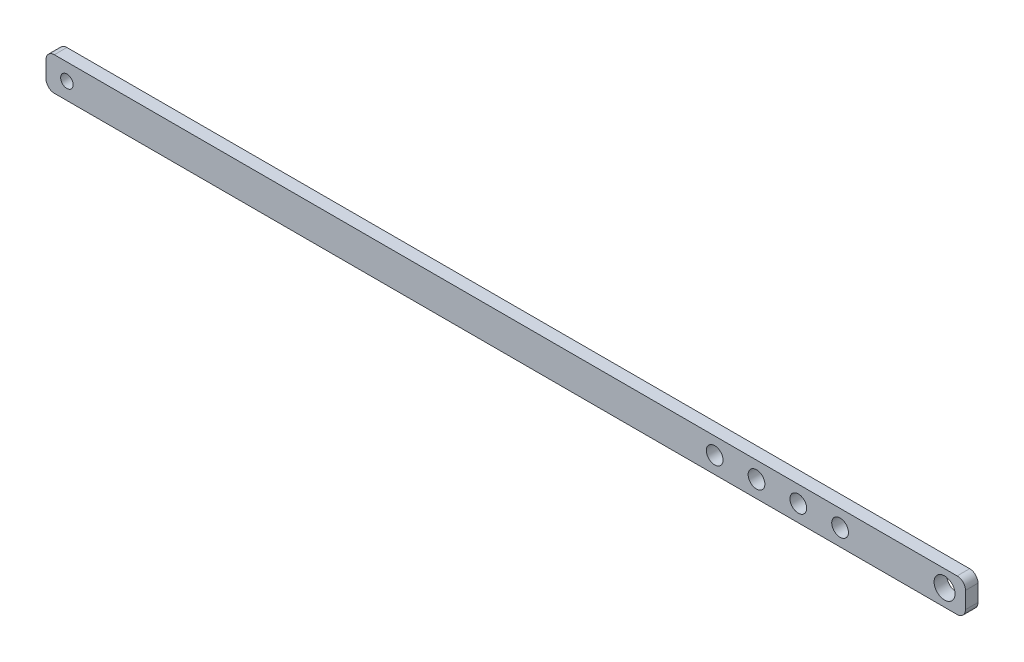
SolidWorks part; units mm, degrees
material "2014 Alloy"
ref_plane "Front Plane" through (0, 0, 0) normal (0, 0, 1) x (1, 0, 0)
ref_plane "Top Plane" through (0, 0, 0) normal (0, 1, 0) x (1, 0, 0)
ref_plane "Right Plane" through (0, 0, 0) normal (1, 0, 0) x (0, 0, -1)
sketch "Sketch1" plane through (0, 0, 0) normal (0, 0, 1) x (1, 0, 0)
  line L1 (-110, -4) -> (110, -4)
  line L2 (-110, -4) -> (-110, 4)
  line L3 (-110, 4) -> (110, 4)
  line L4 (110, -4) -> (110, 4)
  line L5 (-110, -4) -> (110, 4) construction
  line L6 (-110, 4) -> (110, -4) construction
  point P0 (0, 0)
  dimension "D1" = 220
  dimension "D2" = 8
extrude "Boss-Extrude1" add sketch "Sketch1" along normal blind 3
fillet "Fillet1" radius 2 4 edges at (110, -4, 1.5) (110, 4, 1.5) (-110, -4, 1.5) (-110, 4, 1.5)
sketch "Sketch2" plane through (0, 0, 3) normal (0, 0, 1) x (1, 0, 0)
  line L0 (-110, 2) -> (-110, -2) construction
  line L1 (-108, -4) -> (108, -4) construction
  circle A0 centre (-105, 0) radius 1.5
  dimension "D1" = 3
  dimension "D2" = 5
  dimension "D3" = 4
extrude "Cut-Extrude1" cut sketch "Sketch2" against normal up to surface (3 mm away) up to face at (0, 0, 0)
sketch "Sketch3" plane through (0, 0, 3) normal (0, 0, 1) x (1, 0, 0)
  line L3 (-108, -4) -> (108, -4) construction
  line L5 (110, -2) -> (110, 2) construction
  circle A0 centre (105, 0) radius 2.5
  point P7 (110, 0)
  dimension "D3" = 5
  dimension "D1" = 4
  dimension "D2" = 5
extrude "Cut-Extrude2" cut sketch "Sketch3" against normal up to surface (3 mm away) contours A0 up to face at (-106.5, 0, 0)
sketch "Sketch4" plane through (0, 0, 3) normal (0, 0, 1) x (1, 0, 0)
  line L0 (108, 4) -> (-108, 4) construction
  line L1 (110, -2) -> (110, 2) construction
  circle A0 centre (80, 0) radius 2
  point P6 (110, 0)
  dimension "D1" = 4
  dimension "D2" = 4
  dimension "D3" = 30
extrude "Cut-Extrude3" cut sketch "Sketch4" against normal up to surface (3 mm away) up to face at (102.5, 0, 0)
pattern_linear "LPattern1" count 4 spacing 10 along (-1, 0, 0) of "Cut-Extrude3"
